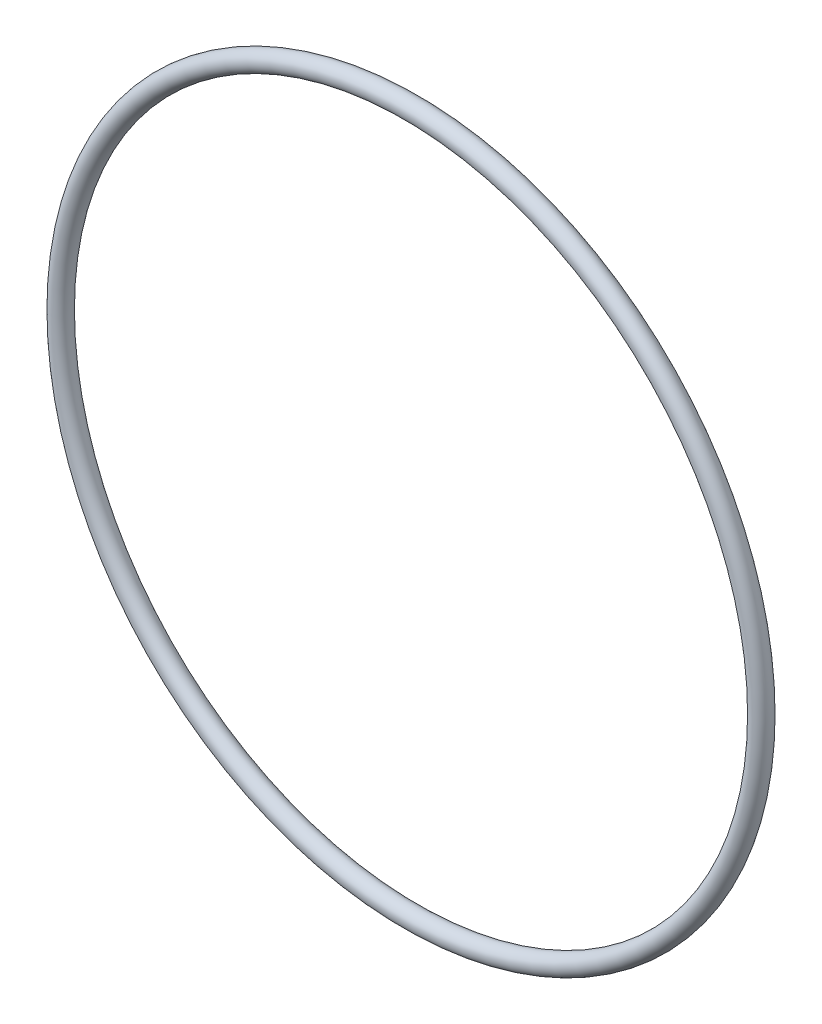
SolidWorks part; units mm, degrees
ref_plane "Front" through (0, 0, 0) normal (0, 0, 1) x (1, 0, 0)
ref_plane "Top" through (0, 0, 0) normal (0, 1, 0) x (1, 0, 0)
ref_plane "Right" through (0, 0, 0) normal (1, 0, 0) x (0, 0, -1)
sketch "Sketch1" plane through (0, 0, 0) normal (1, 0, 0) x (0, -1, 0)
  line L0 (0, -3) -> (0, 3) construction
  line L2 (-125.4, 0) -> (125.4, 0) construction
  line L3 (-105, 0) -> (105, 0) construction
  circle A0 centre (108, 0) radius 3
  point P9 (105, 0)
  point P10 (111, 0)
  point P13 (108, 3)
  point P14 (108, -3)
  dimension "Width" = 6
  dimension "ID" = 210
revolve "Revolve1" add sketch "Sketch1" angle 360 about L0
